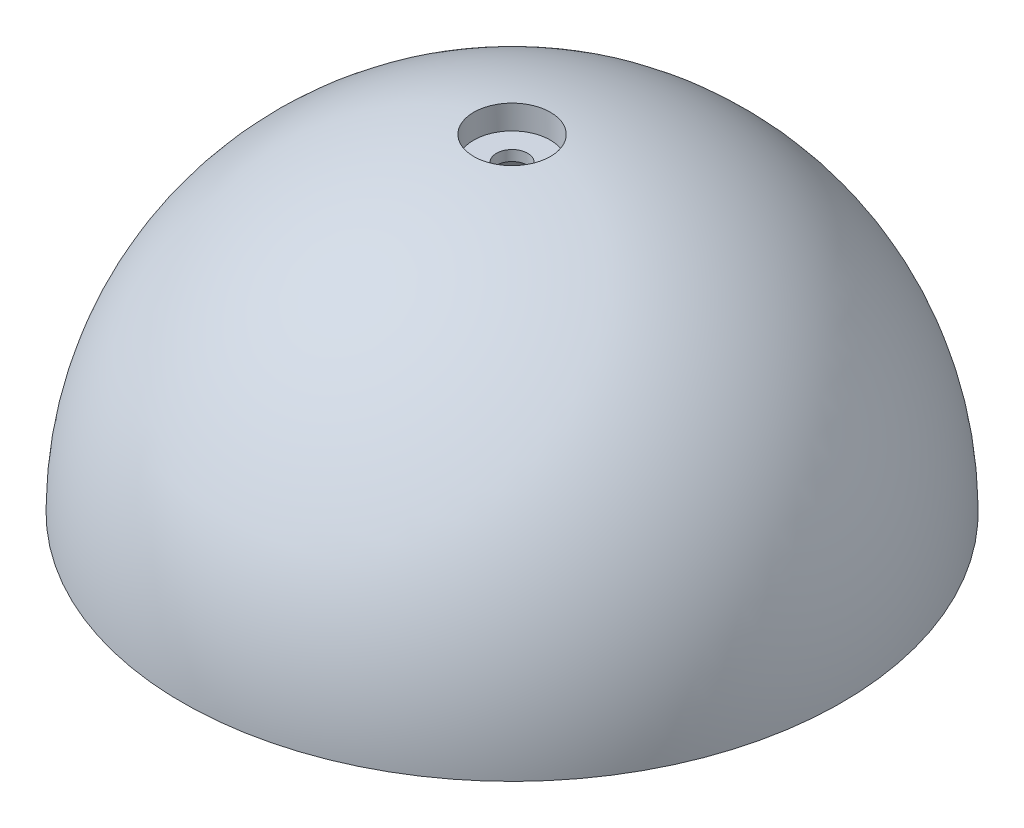
SolidWorks part; units mm, degrees
ref_plane "Front Plane" through (0, 0, 0) normal (0, 0, 1) x (1, 0, 0)
ref_plane "Top Plane" through (0, 0, 0) normal (0, 1, 0) x (1, 0, 0)
ref_plane "Right Plane" through (0, 0, 0) normal (1, 0, 0) x (0, 0, -1)
sketch "Half Circle" plane through (0, 0, 0) normal (0, 0, 1) x (1, 0, 0)
  line L2 (0, 85) -> (0, 95)
  line L3 (0, -85) -> (0, -95)
  line L4 (0, -85) -> (0, 85) construction
  arc A0 (0, 95) -> (0, -95) centre (0, 0) ccw
  arc A1 (0, 85) -> (0, -85) centre (0, 0) ccw
  dimension "D1" = 190
  dimension "D2" = 10
revolve "Sphere Revolve" add sketch "Half Circle" angle 360 about L2
sketch "Sketch2" plane through (0, 0, 0) normal (0, 1, 0) x (1, 0, 0)
  line L1 (-121.3228, -115.569) -> (121.3228, -115.569)
  line L2 (-121.3228, -115.569) -> (-121.3228, 115.569)
  line L3 (-121.3228, 115.569) -> (121.3228, 115.569)
  line L4 (121.3228, -115.569) -> (121.3228, 115.569)
  line L5 (-121.3228, -115.569) -> (121.3228, 115.569) construction
  line L6 (-121.3228, 115.569) -> (121.3228, -115.569) construction
  point P0 (0, 0)
extrude "Cut in Half" cut sketch "Sketch2" against normal through all
sketch "Sketch3" plane through (0, 0, 0) normal (0, 1, 0) x (1, 0, 0)
  line L0 (0, -95) -> (0, 95) construction
  circle A0 centre (0, 0) radius 11
  circle A1 centre (0, 0) radius 95 construction
  dimension "D1" = 22
  dimension "D2" = 190
extrude "BallBearingHole" cut sketch "Sketch3" along normal through all
ref_plane "SupportForHolePlane" through (0, 84.4, 0) normal (0, 1, 0) x (1, 0, 0)
sketch "Sketch4" plane through (0, 84.4, 0) normal (0, 1, 0) x (1, 0, 0)
  circle A0 centre (0, 0) radius 31.2029
extrude "SupportForHole" add sketch "Sketch4" along normal blind 4
ref_plane "TopPlane" through (0, 94.4, 0) normal (0, 1, 0) x (1, 0, 0)
sketch "Sketch5" plane through (0, 94.4, 0) normal (0, 1, 0) x (1, 0, 0)
  circle A0 centre (0, 0) radius 11.05
extrude "2ndBearingHole" cut sketch "Sketch5" against normal blind 7
sketch "Sketch6" plane through (0, 87.4, 0) normal (0, 1, 0) x (1, 0, 0)
  circle A0 centre (0, 0) radius 4.5
  dimension "D1" = 9
extrude "InsideHole" cut sketch "Sketch6" against normal through all
